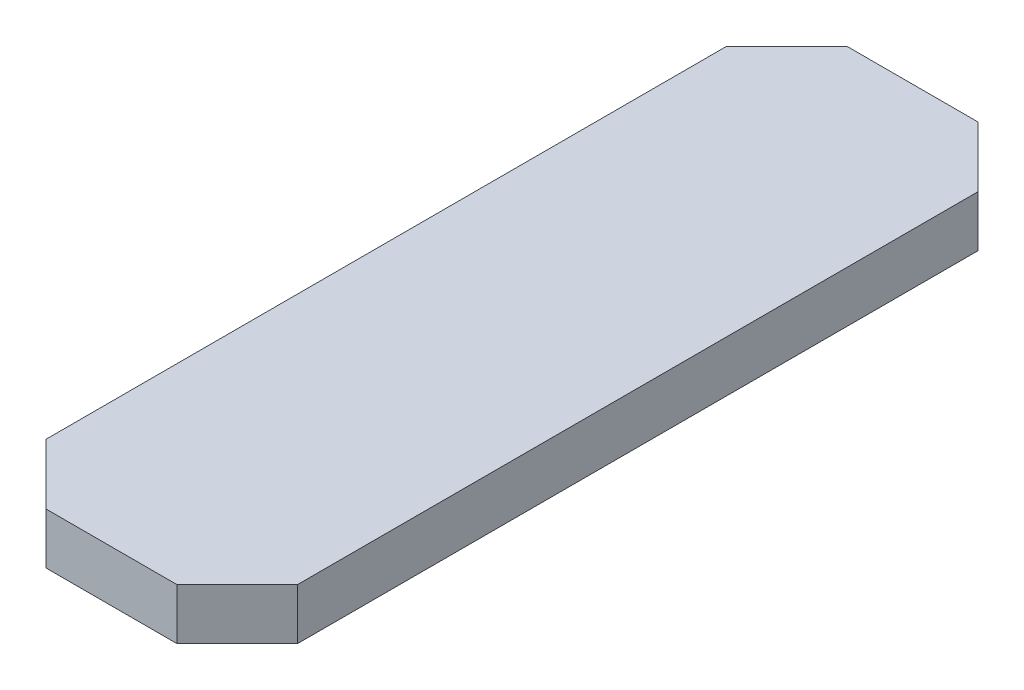
SolidWorks part; units mm, degrees
ref_plane "Front Plane" through (0, 0, 0) normal (0, 0, 1) x (1, 0, 0)
ref_plane "Top Plane" through (0, 0, 0) normal (0, 1, 0) x (1, 0, 0)
ref_plane "Right Plane" through (0, 0, 0) normal (1, 0, 0) x (0, 0, -1)
sketch "Sketch1" plane through (0, 0, 0) normal (0, 1, 0) x (1, 0, 0)
  line L1 (-62.5, 199) -> (62.5, 199)
  line L2 (-62.5, 199) -> (-62.5, -199)
  line L3 (-62.5, -199) -> (62.5, -199)
  line L4 (62.5, 199) -> (62.5, -199)
  line L5 (-62.5, 199) -> (62.5, -199) construction
  line L6 (-62.5, -199) -> (62.5, 199) construction
  point P0 (0, 0)
  dimension "D1" = 398
  dimension "D2" = 125
extrude "Boss-Extrude1" add sketch "Sketch1" along normal blind 25.4
chamfer "Chamfer1" distance 30 angle 45 4 edges at (-62.5, 12.7, -199) (62.5, 12.7, -199) (62.5, 12.7, 199) (-62.5, 12.7, 199)
